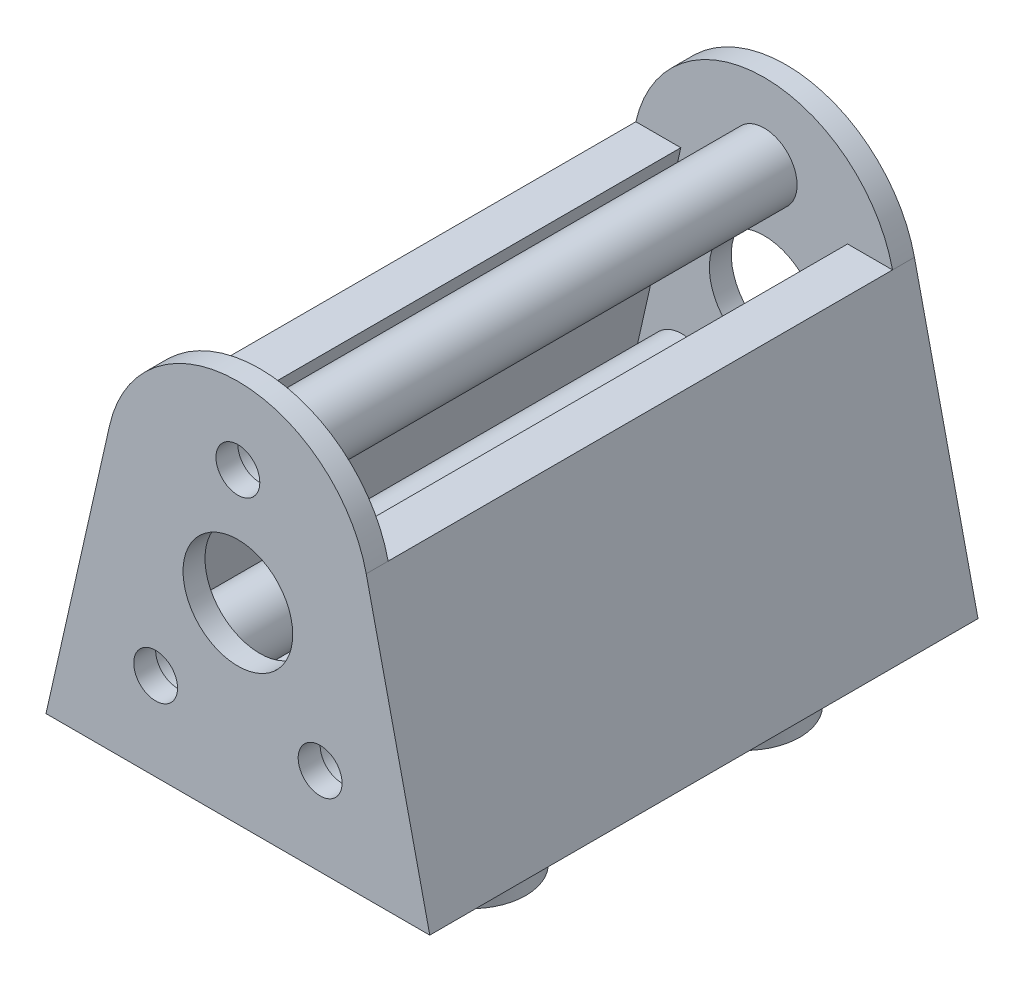
SolidWorks part; units mm, degrees
ref_plane "Front Plane" through (0, 0, 0) normal (0, 0, 1) x (1, 0, 0)
ref_plane "Top Plane" through (0, 0, 0) normal (0, 1, 0) x (1, 0, 0)
ref_plane "Right Plane" through (0, 0, 0) normal (1, 0, 0) x (0, 0, -1)
sketch "Sketch1" plane through (0, 0, 0) normal (0, 0, 1) x (1, 0, 0)
  line L0 (-17.5, 0) -> (17.5, 0)
  line L1 (0, 0) -> (0, 35) construction
  line L2 (17.5, 0) -> (11.7049, 25.645)
  line L3 (-17.5, 0) -> (-11.7049, 25.645)
  line L4 (-7.5, 8) -> (7.5, 8)
  arc A0 (11.7049, 25.645) -> (-11.7049, 25.645) centre (0, 23) ccw
  circle A1 centre (0, 17.5) radius 5
  circle A2 centre (7.5, 8) radius 2
  circle A3 centre (-7.5, 8) radius 2
  circle A4 centre (0, 28) radius 2
  point P4 (0, 0)
  point P17 (0, 8)
  dimension "D3" = 24
  dimension "D4" = 10
  dimension "D5" = 4
  dimension "D6" = 15
  dimension "D8" = 4
  dimension "D1" = 35
  dimension "D2" = 35
  dimension "D7" = 8
  dimension "D9" = 7
extrude "Boss-Extrude1" add sketch "Sketch1" along normal blind 2
ref_plane "Plane1" through (0, 0, -48) normal (0, 0, 1) x (1, 0, 0)
sketch "Sketch2" plane through (0, 0, -48) normal (0, 0, 1) x (1, 0, 0)
  line L3 (17.5, 0) -> (11.7049, 25.645)
  line L4 (-17.5, 0) -> (17.5, 0)
  line L5 (-11.7049, 25.645) -> (-17.5, 0)
  line L6 (17.5, 0) -> (11.7049, 25.645)
  line L7 (-17.5, 0) -> (17.5, 0)
  line L8 (-11.7049, 25.645) -> (-17.5, 0)
  circle A0 centre (-7.5, 8) radius 2 construction
  arc A1 (11.7049, 25.645) -> (-11.7049, 25.645) centre (0, 23) ccw
  arc A2 (11.7049, 25.645) -> (-11.7049, 25.645) centre (0, 23) ccw
  circle A3 centre (7.5, 8) radius 2 construction
  circle A4 centre (0, 17.5) radius 5 construction
  circle A5 centre (0, 28) radius 2 construction
  circle A6 centre (-7.5, 8) radius 2
  circle A7 centre (7.5, 8) radius 2
  circle A8 centre (0, 17.5) radius 5
  circle A9 centre (0, 28) radius 2
  dimension "D1" = 0
extrude "Boss-Extrude2" add sketch "Sketch2" along normal blind 2 separate body
sketch "Sketch3" plane through (0, 0, 0) normal (0, 0, -1) x (-1, 0, 0)
  line L0 (16.5961, 4) -> (-16.5961, 4)
  line L1 (16.5961, 4) -> (17.5, 0)
  line L2 (-16.5961, 4) -> (-17.5, 0)
  line L3 (-11.7049, 25.645) -> (-17.5, 0)
  line L4 (-17.5, 0) -> (17.5, 0)
  line L5 (17.5, 0) -> (11.7049, 25.645)
  line L6 (-11.7049, 25.645) -> (-17.5, 0)
  line L7 (-17.5, 0) -> (17.5, 0)
  line L8 (17.5, 0) -> (11.7049, 25.645)
  line L9 (12.4952, 4) -> (7.604, 25.645)
  line L10 (13.5984, -0.8817) -> (7.8032, 24.7633) construction
  line L11 (11.7049, 25.645) -> (7.604, 25.645)
  line L12 (0, 0) -> (0, 60.152) construction
  line L13 (-17.5, 0) -> (-11.7049, 25.645)
  line L14 (-11.7049, 25.645) -> (-7.604, 25.645)
  line L15 (-12.4952, 4) -> (-7.604, 25.645)
  arc A1 (11.7049, 25.645) -> (-11.7049, 25.645) centre (0, 23) ccw
  arc A2 (11.7049, 25.645) -> (-11.7049, 25.645) centre (0, 23) ccw
  line M10 (-11.7049, 25.645) -> (-17.5, 0)
  line M11 (-17.5, 0) -> (17.5, 0)
  line M12 (17.5, 0) -> (11.7049, 25.645)
  dimension "D2" = 4
  dimension "D3" = 4
  dimension "D1" = 0
sketch "Sketch4" plane through (0, 0, 0) normal (0, 0, -1) x (-1, 0, 0)
  line L0 (0, 0) -> (0, 21.9621) construction
  line L1 (0, 0) -> (0, 60.152) construction
  circle A1 centre (7.5, 8) radius 3
  circle A2 centre (7.5, 8) radius 2.5
  circle A3 centre (0, 28) radius 3
  circle A4 centre (0, 28) radius 2.5
  circle A5 centre (-7.5, 8) radius 3
  circle A6 centre (-7.5, 8) radius 2.5
  dimension "D1" = 6
  dimension "D3" = 6
  dimension "D2" = 0.5
  dimension "D4" = 0.5
extrude "Boss-Extrude4" add sketch "Sketch4" along normal up to surface (46 mm away) up to face at (5, 17.5, -46)
extrude "Boss-Extrude5" add sketch "Sketch3" along normal up to surface (48 mm away) contours L11 L9 L0 M12 | L0 L15 L14 M10 | L0 M12 M10 M11 up to plane "Plane1"
sketch "Sketch6" plane through (0, 0, 2) normal (0, 0, 1) x (1, 0, 0)
  circle A0 centre (0, 17.5) radius 2.6054
ref_plane "Plane2" through (0, 17.5, 0) normal (0, 1, 0) x (1, 0, 0)
sketch "Sketch7" plane through (0, 17.5, 0) normal (0, 1, 0) x (1, 0, 0)
  line L0 (0, -2) -> (0, 23) construction
  line L1 (-2.6054, -2) -> (2.6054, -2) construction
sketch "Sketch8" plane through (0, 0, 0) normal (0, -1, 0) x (1, 0, 0)
  line L0 (0, 2) -> (0, -48) construction
  line L1 (-17.5, -48) -> (17.5, -48) construction
  line L2 (0, -23) -> (17.5, -23) construction
  line L3 (17.5, 2) -> (17.5, -48) construction
  line L4 (8.75, -23) -> (8.75, 2) construction
  line L5 (-17.5, 2) -> (17.5, 2) construction
  circle A0 centre (8.75, -10.5) radius 5
  circle A1 centre (8.75, -10.5) radius 2.5
  circle A2 centre (8.75, -35.5) radius 2.5
  circle A3 centre (8.75, -35.5) radius 5
  circle A4 centre (-8.75, -35.5) radius 2.5
  circle A5 centre (-8.75, -35.5) radius 5
  circle A6 centre (-8.75, -10.5) radius 2.5
  circle A7 centre (-8.75, -10.5) radius 5
  dimension "D1" = 10
  dimension "D2" = 5
extrude "Boss-Extrude6" add sketch "Sketch8" along normal blind 5
